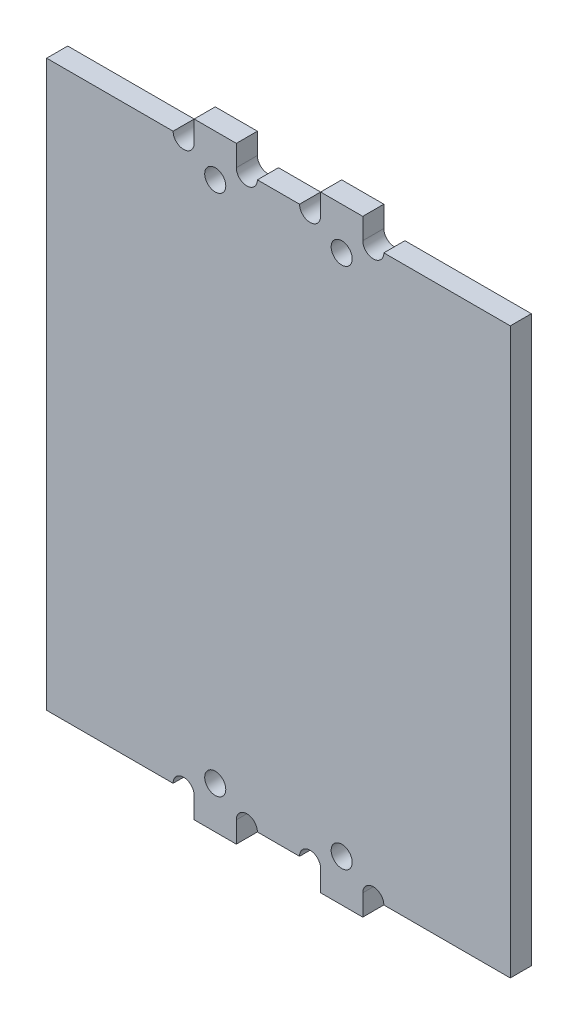
SolidWorks part; units mm, degrees
material "自訂玻璃纖維"
ref_plane "前基準面" through (0, 0, 0) normal (0, 0, 1) x (1, 0, 0)
ref_plane "上基準面" through (0, 0, 0) normal (0, 1, 0) x (1, 0, 0)
ref_plane "右基準面" through (0, 0, 0) normal (1, 0, 0) x (0, 0, -1)
sketch "草圖1" plane through (0, 0, 0) normal (0, 0, 1) x (1, 0, 0)
  line L0 (-13.6555, 25.9798) -> (-13.6555, 26.9798)
  line L1 (-12.6555, 26.9798) -> (-1.6555, 26.9798)
  line L2 (-13.6555, 25.9798) -> (-13.6555, -26.6202)
  line L3 (-12.6555, -26.6202) -> (-1.6555, -26.6202)
  line L4 (30.3445, 25.9798) -> (30.3445, -26.6202)
  line L5 (-13.6555, 26.9798) -> (-12.6555, 26.9798)
  line L6 (6.3445, -26.6202) -> (10.3445, -26.6202)
  line L7 (30.3445, 25.9798) -> (30.3445, 26.9798)
  line L8 (30.3445, 26.9798) -> (29.3445, 26.9798)
  line L9 (16.3445, -26.6202) -> (16.3445, -28.6202)
  line L10 (30.3445, -26.6202) -> (29.3445, -26.6202)
  line L11 (0.3445, 26.9798) -> (0.3445, 28.9798)
  line L12 (-13.6555, -26.6202) -> (-12.6555, -26.6202)
  line L13 (0.3445, 28.9798) -> (4.3445, 28.9798)
  line L14 (4.3445, 26.9798) -> (4.3445, 28.9798)
  line L15 (6.3445, 26.9798) -> (10.3445, 26.9798)
  line L16 (12.3445, 26.9798) -> (12.3445, 28.9798)
  line L17 (12.3445, 28.9798) -> (16.3445, 28.9798)
  line L18 (12.3445, -28.6202) -> (16.3445, -28.6202)
  line L19 (16.3445, 26.9798) -> (16.3445, 28.9798)
  line L20 (12.3445, -26.6202) -> (12.3445, -28.6202)
  line L21 (18.3445, 26.9798) -> (29.3445, 26.9798)
  line L23 (4.3445, -26.6202) -> (4.3445, -28.6202)
  line L24 (0.3445, -28.6202) -> (4.3445, -28.6202)
  line L25 (0.3445, -26.6202) -> (0.3445, -28.6202)
  line L26 (18.3445, -26.6202) -> (29.3445, -26.6202)
  arc A0 (0.3445, 26.9798) -> (-1.6555, 26.9798) centre (-0.6555, 26.9798) cw
  circle A1 centre (14.3445, 24.9798) radius 1
  circle A2 centre (2.3445, -24.6202) radius 1
  circle A3 centre (14.3445, -24.6202) radius 1
  circle A4 centre (2.3445, 24.9798) radius 1
  arc A5 (4.3445, 26.9798) -> (6.3445, 26.9798) centre (5.3445, 26.9798) ccw
  arc A6 (16.3445, 26.9798) -> (18.3445, 26.9798) centre (17.3445, 26.9798) ccw
  arc A7 (12.3445, 26.9798) -> (10.3445, 26.9798) centre (11.3445, 26.9798) cw
  arc A8 (12.3445, -26.6202) -> (10.3445, -26.6202) centre (11.3445, -26.6202) ccw
  arc A9 (16.3445, -26.6202) -> (18.3445, -26.6202) centre (17.3445, -26.6202) cw
  arc A10 (4.3445, -26.6202) -> (6.3445, -26.6202) centre (5.3445, -26.6202) cw
  arc A11 (0.3445, -26.6202) -> (-1.6555, -26.6202) centre (-0.6555, -26.6202) ccw
  point P10 (-13.6555, -26.6202)
  point P15 (30.3445, 26.9798)
  point P18 (-13.6555, 26.9798)
  dimension "D4" = 2
  dimension "D5" = 49.6
  dimension "D6" = 12
  dimension "D7" = 2
  dimension "D9" = 2
  dimension "D1" = 44
  dimension "D2" = 53.6
  dimension "D8" = 4
extrude "填料-伸長1" add sketch "草圖1" along normal blind 2
